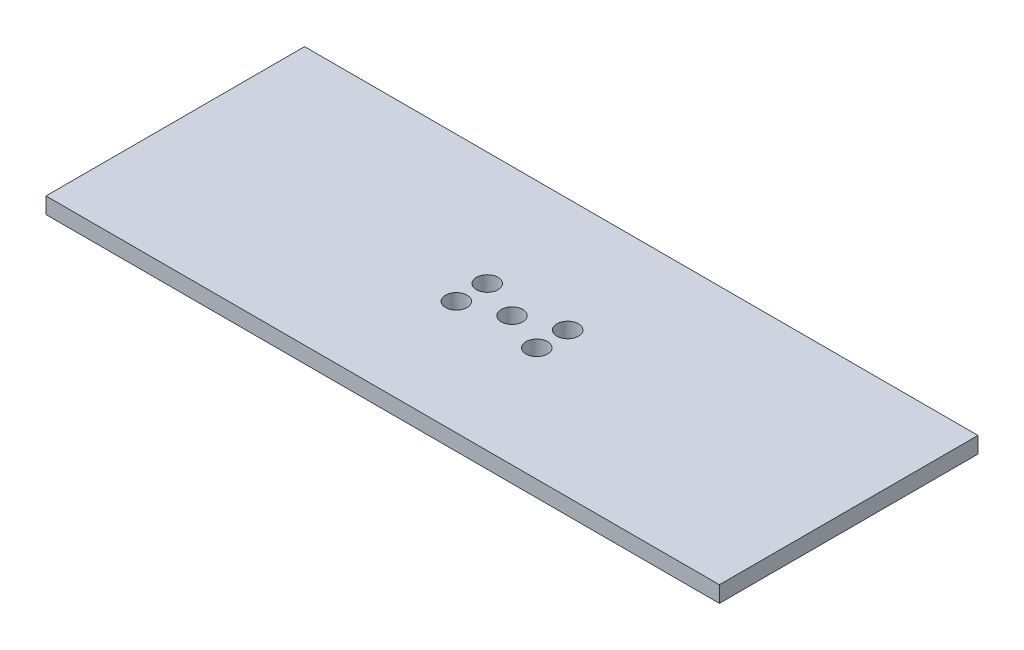
SolidWorks part; units mm, degrees
ref_plane "Front Plane" through (0, 0, 0) normal (0, 0, 1) x (1, 0, 0)
ref_plane "Top Plane" through (0, 0, 0) normal (0, 1, 0) x (1, 0, 0)
ref_plane "Right Plane" through (0, 0, 0) normal (1, 0, 0) x (0, 0, -1)
sketch "Sketch1" plane through (0, 0, 0) normal (0, 1, 0) x (1, 0, 0)
  line L1 (-62.5, -24) -> (62.5, -24)
  line L2 (-62.5, -24) -> (-62.5, 24)
  line L3 (-62.5, 24) -> (62.5, 24)
  line L4 (62.5, -24) -> (62.5, 24)
  line L5 (-62.5, -24) -> (62.5, 24) construction
  line L6 (-62.5, 24) -> (62.5, -24) construction
  circle A0 centre (0, 0) radius 2
  circle A1 centre (-7.4683, 2.8678) radius 2
  circle A2 centre (7.4683, -2.8678) radius 2
  circle A3 centre (-7.4683, -2.8678) radius 2
  circle A4 centre (7.4683, 2.8678) radius 2
  point P0 (0, 0)
  dimension "D3" = 4
  dimension "D4" = 4
  dimension "D6" = 4
  dimension "D8" = 4
  dimension "D9" = 4
  dimension "D1" = 125
  dimension "D2" = 48
  dimension "D5" = 8
  dimension "D7" = 8
  dimension "D10" = 8
  dimension "D11" = 8
extrude "Boss-Extrude1" add sketch "Sketch1" along normal blind 3
